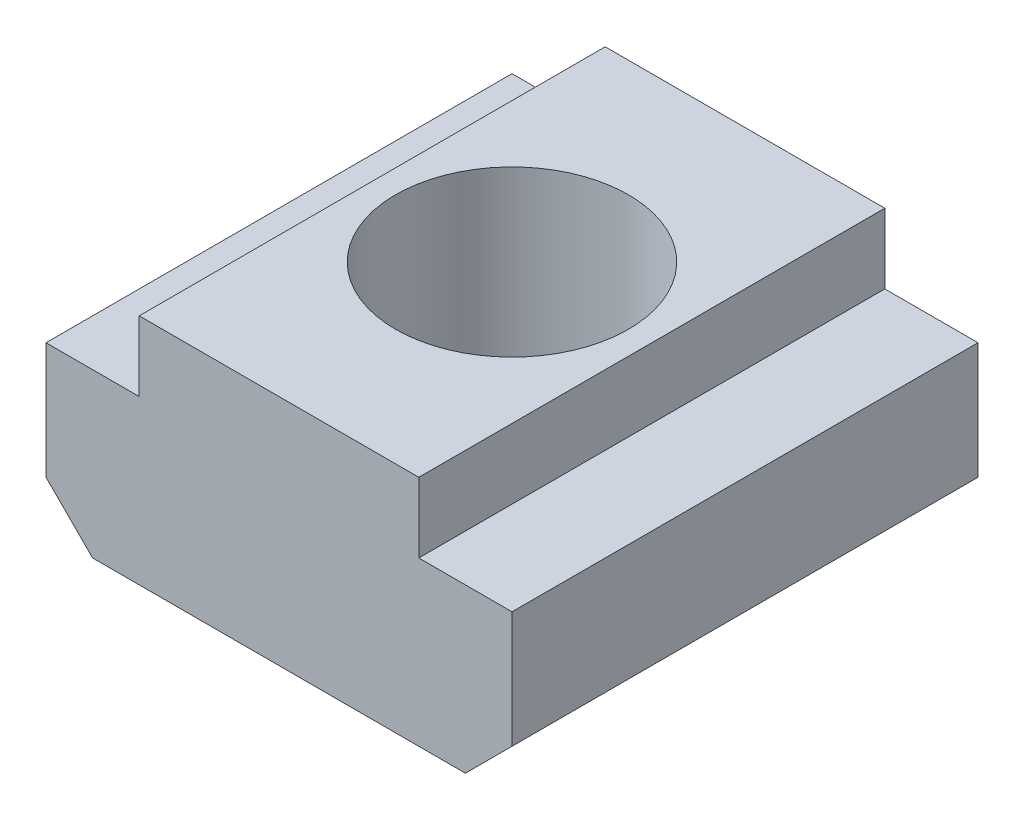
SolidWorks part; units mm, degrees
ref_plane "Front Plane" through (0, 0, 0) normal (0, 0, 1) x (1, 0, 0)
ref_plane "Top Plane" through (0, 0, 0) normal (0, 1, 0) x (1, 0, 0)
ref_plane "Right Plane" through (0, 0, 0) normal (1, 0, 0) x (0, 0, -1)
sketch "Sketch1" plane through (0, 0, 0) normal (0, 0, 1) x (1, 0, 0)
  line L0 (0, 0) -> (0, 46.9655) construction
  line L1 (-4, 0) -> (4, 0)
  line L2 (4, 0) -> (5, 1)
  line L3 (5, 1) -> (5, 3.5)
  line L4 (5, 3.5) -> (3, 3.5)
  line L5 (3, 3.5) -> (3, 5)
  line L6 (3, 5) -> (-3, 5)
  line L7 (-3, 5) -> (-3, 3.5)
  line L8 (-3, 3.5) -> (-5, 3.5)
  line L9 (-5, 3.5) -> (-5, 1)
  line L10 (-5, 1) -> (-4, 0)
  point P10 (0, 5)
  point P14 (-5, 2.25)
  dimension "D1" = 6
  dimension "D2" = 10
  dimension "D3" = 5
  dimension "D4" = 1.5
  dimension "D5" = 5
  dimension "D6" = 1
  dimension "D7" = 1
  dimension "D8" = 1
extrude "Boss-Extrude1" add sketch "Sketch1" along normal blind 10
sketch "Sketch2" plane through (0, 5, 0) normal (0, 1, 0) x (1, 0, 0)
  line L0 (-3, 0) -> (3, -10) construction
  point P4 (0, -5)
hole_wizard "M6x1.0 Tapped Hole1" positions "Sketch3" profile "Sketch4" tap size "M6x1.0" standard "ANSI Metric" end condition through all
sketch "Sketch3" plane through (0, 5, 0) normal (0, 1, 0) x (1, 0, 0)
  point P0 (0, -5)
sketch "Sketch4" plane through (0, 5, 5) normal (1, 0, 0) x (0, 0, 1)
  line L0 (0, 0) -> (0, 5)
  line L1 (0, 5) -> (2.5, 5)
  line L2 (2.5, 5) -> (2.5, 0)
  line L5 (2.5, 0) -> (0, 0)
  line L11 (0, -6.35) -> (0, 107.95) construction
  dimension "Thru Tap Drill Dia." = 5
  dimension "Thru Tap Drill Depth" = 5
cosmetic thread "Hole Thread1" parameters "D2"=6
